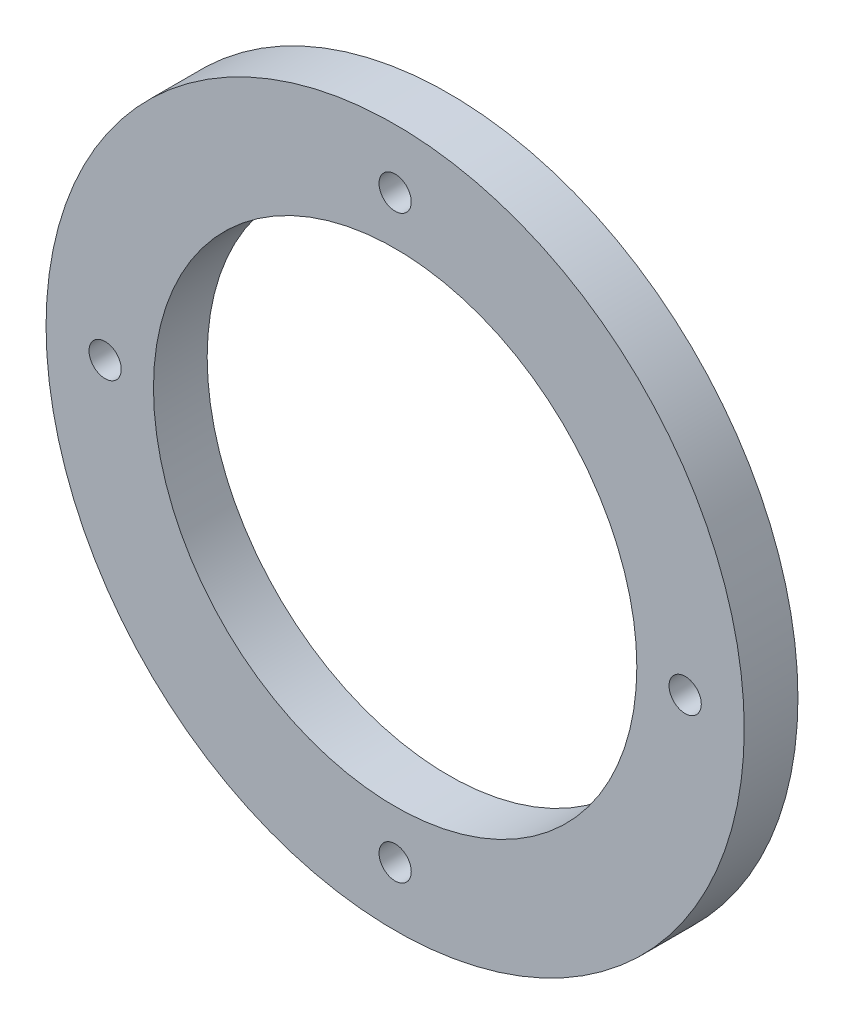
SolidWorks part; units mm, degrees
ref_plane "Front Plane" through (0, 0, 0) normal (0, 0, 1) x (1, 0, 0)
ref_plane "Top Plane" through (0, 0, 0) normal (0, 1, 0) x (1, 0, 0)
ref_plane "Right Plane" through (0, 0, 0) normal (1, 0, 0) x (0, 0, -1)
sketch "Sketch1" plane through (0, 0, 0) normal (0, 0, 1) x (1, 0, 0)
  circle A0 centre (0, 0) radius 32.5
  circle A1 centre (0, 0) radius 22.5
  circle A2 centre (27, 0) radius 1.5
  circle A3 centre (0, 27) radius 1.5
  circle A5 centre (0, -27) radius 1.5
  circle A6 centre (-27, 0) radius 1.5
  dimension "D1" = 3
  dimension "D2" = 3
  dimension "D3" = 3
  dimension "D4" = 3
  dimension "D5" = 65
  dimension "D6" = 45
  dimension "D7" = 27
  dimension "D8" = 27
  dimension "D9" = 27
  dimension "D10" = 27
extrude "Boss-Extrude1" add sketch "Sketch1" along normal blind 5
